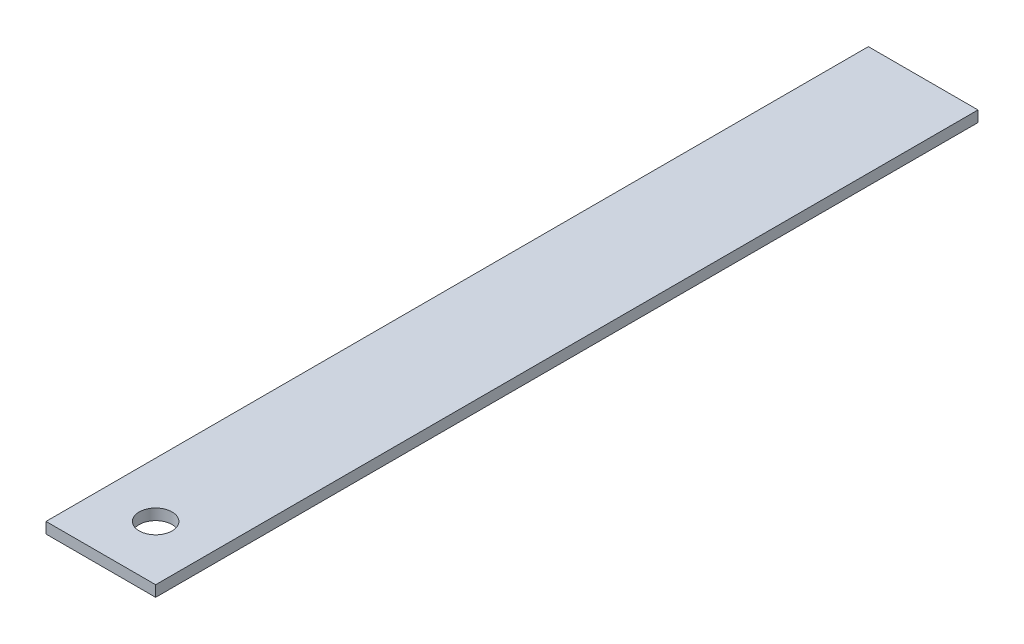
SolidWorks part; units mm, degrees
ref_plane "Front Plane" through (0, 0, 0) normal (0, 0, 1) x (1, 0, 0)
ref_plane "Top Plane" through (0, 0, 0) normal (0, 1, 0) x (1, 0, 0)
ref_plane "Right Plane" through (0, 0, 0) normal (1, 0, 0) x (0, 0, -1)
sketch "Sketch1" plane through (0, 0, 0) normal (0, 1, 0) x (1, 0, 0)
  line L0 (0, 75) -> (0, -75) construction
  line L1 (-10, -75) -> (10, -75)
  line L2 (-10, -75) -> (-10, 75)
  line L3 (-10, 75) -> (10, 75)
  line L4 (10, -75) -> (10, 75)
  line L5 (-10, -75) -> (10, 75) construction
  line L6 (-10, 75) -> (10, -75) construction
  circle A0 centre (0, -65) radius 3
  point P0 (0, 0)
  dimension "D3" = 6
  dimension "D4" = 10
  dimension "D1" = 20
  dimension "D2" = 150
extrude "Boss-Extrude1" add sketch "Sketch1" along normal blind 2
